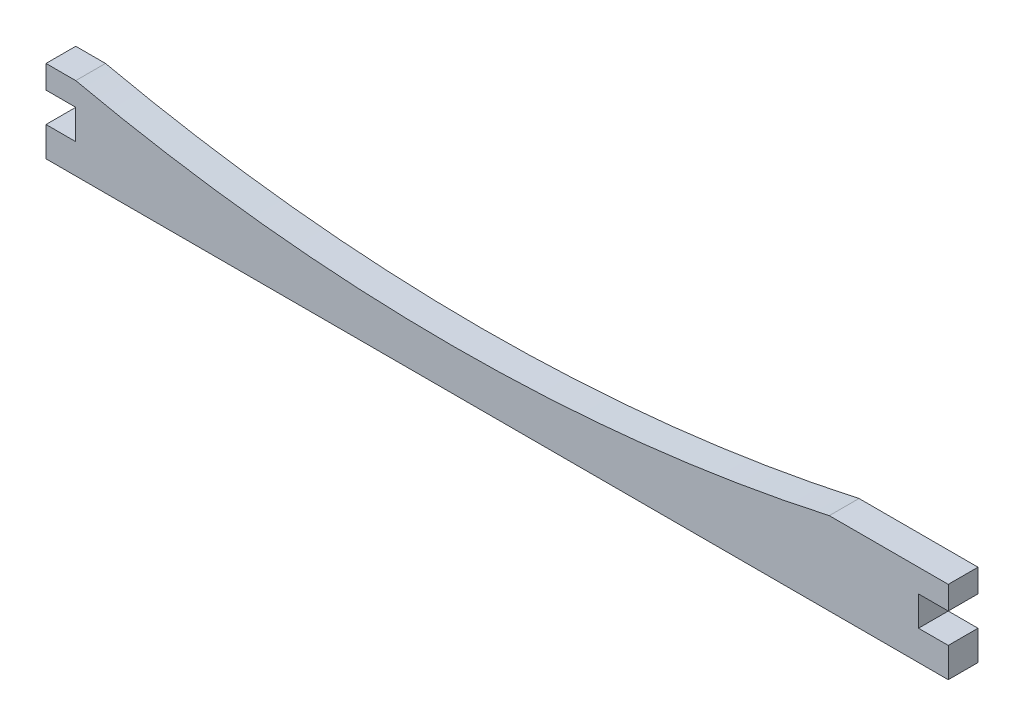
SolidWorks part; units mm, degrees
ref_plane "Front Plane" through (0, 0, 0) normal (0, 0, 1) x (1, 0, 0)
ref_plane "Top Plane" through (0, 0, 0) normal (0, 1, 0) x (1, 0, 0)
ref_plane "Right Plane" through (0, 0, 0) normal (1, 0, 0) x (0, 0, -1)
sketch "Sketch1" plane through (0, 0, 0) normal (0, 0, 1) x (1, 0, 0)
  line L0 (-123, 0) -> (123, 0)
  line L1 (-123, 0) -> (-123, 25)
  line L3 (123, 25) -> (123, 0)
  line L4 (-114, 25) -> (-114, 0) construction
  line L5 (114, 25) -> (114, 0) construction
  line L6 (-123, 25) -> (-114, 25)
  line L7 (123, 25) -> (114, 25)
  line L8 (-114, 25) -> (114, 25) construction
  line L9 (-114, 12.5) -> (114, 12.5) construction
  circle A0 centre (0, 538.59) radius 526.09
  dimension "D1" = 246
  dimension "D2" = 25
  dimension "D3" = 9
  dimension "D4" = 9
extrude "Boss-Extrude2" add sketch "Sketch1" along normal blind 9 contours A0 L6 L1 L0 L3 L7
sketch "Sketch2" plane through (0, 0, 0) normal (0, 0, 1) x (1, 0, 0)
  line L0 (123, 25) -> (123, 0) construction
  line L1 (123, 18) -> (114, 18)
  line L2 (123, 18) -> (123, 9)
  line L3 (123, 9) -> (114, 9)
  line L4 (114, 18) -> (114, 9)
  line L7 (118.5, 25) -> (118.5, 18) construction
  line L9 (123, 25) -> (114, 25) construction
  line L10 (118.5, 18) -> (118.5, 9) construction
  line L11 (118.5, 9) -> (118.5, 0) construction
  line L12 (-123, 0) -> (123, 0) construction
  line L13 (0, 0) -> (0, 12.5) construction
  line L14 (-118.5, 9) -> (-118.5, 0) construction
  line L15 (-118.5, 18) -> (-118.5, 9) construction
  line L16 (-118.5, 25) -> (-118.5, 18) construction
  line L17 (-114, 18) -> (-114, 9)
  line L18 (-123, 9) -> (-114, 9)
  line L19 (-123, 18) -> (-123, 9)
  line L20 (-123, 18) -> (-114, 18)
  arc A0 (-114, 25) -> (114, 25) centre (0, 538.59) ccw construction
  dimension "D1" = 9
  dimension "D2" = 9
  dimension "D3" = 9
extrude "Cut-Extrude1" cut sketch "Sketch2" along normal through all
sketch "Sketch3" plane through (0, 0, 0) normal (0, 0, 1) x (1, 0, 0)
  line L0 (114, 25) -> (114, 0)
  line L1 (-123, 0) -> (123, 0) construction
  line L2 (114, 0) -> (150, 0)
  line L3 (150, 0) -> (150, 9)
  line L4 (150, 9) -> (141, 9)
  line L5 (141, 9) -> (141, 18)
  line L6 (141, 18) -> (150, 18)
  line L7 (150, 18) -> (150, 25)
  line L8 (150, 25) -> (114, 25)
  line L9 (150, 18) -> (150, 9) construction
  line L10 (123, 18) -> (141, 18) construction
  line L11 (141, 9) -> (123, 9) construction
  dimension "D1" = 9
  dimension "D2" = 36
extrude "Boss-Extrude3" add sketch "Sketch3" along normal up to surface (9 mm away) up to face at (0, 13.9643, 9)
